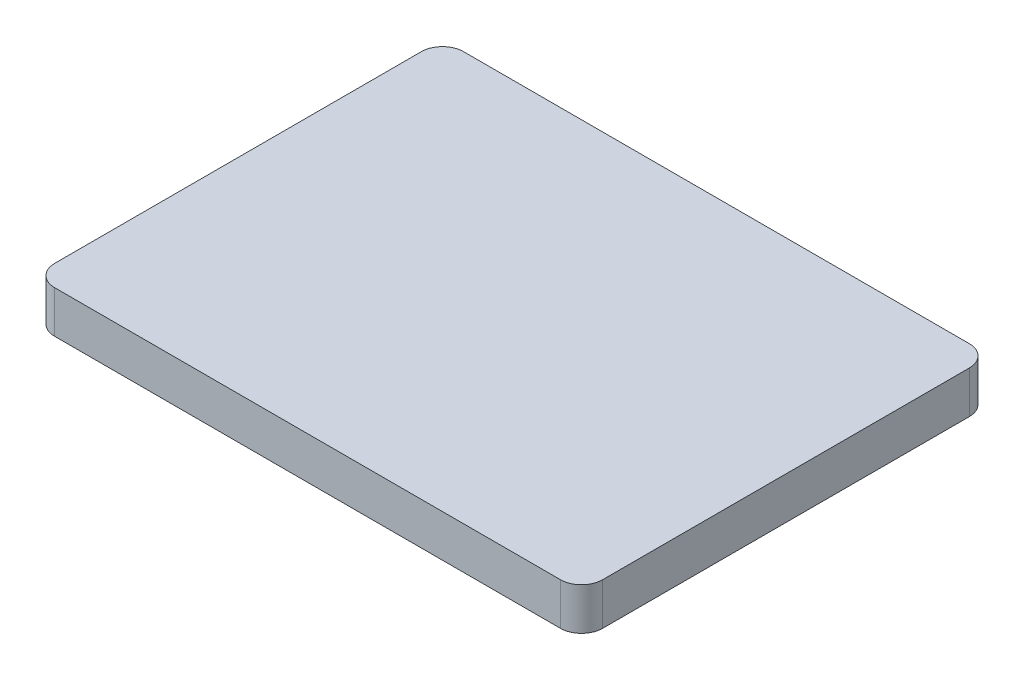
SolidWorks part; units mm, degrees
material "K110"
ref_plane "Front Plane" through (0, 0, 0) normal (0, 0, 1) x (1, 0, 0)
ref_plane "Top Plane" through (0, 0, 0) normal (0, 1, 0) x (1, 0, 0)
ref_plane "Right Plane" through (0, 0, 0) normal (1, 0, 0) x (0, 0, -1)
sketch "Sketch1" plane through (0, 0, 0) normal (0, 1, 0) x (1, 0, 0)
  line L1 (-65, -48.5) -> (65, -48.5)
  line L2 (-65, -48.5) -> (-65, 48.5)
  line L3 (-65, 48.5) -> (65, 48.5)
  line L4 (65, -48.5) -> (65, 48.5)
  line L5 (-65, -48.5) -> (65, 48.5) construction
  line L6 (-65, 48.5) -> (65, -48.5) construction
  point P0 (0, 0)
  dimension "D1" = 130
  dimension "D2" = 97
extrude "Boss-Extrude1" add sketch "Sketch1" against normal blind 10
fillet "Fillet1" radius 5 4 edges at (-65, -5, -48.5) (-65, -5, 48.5) (65, -5, -48.5) (65, -5, 48.5)
